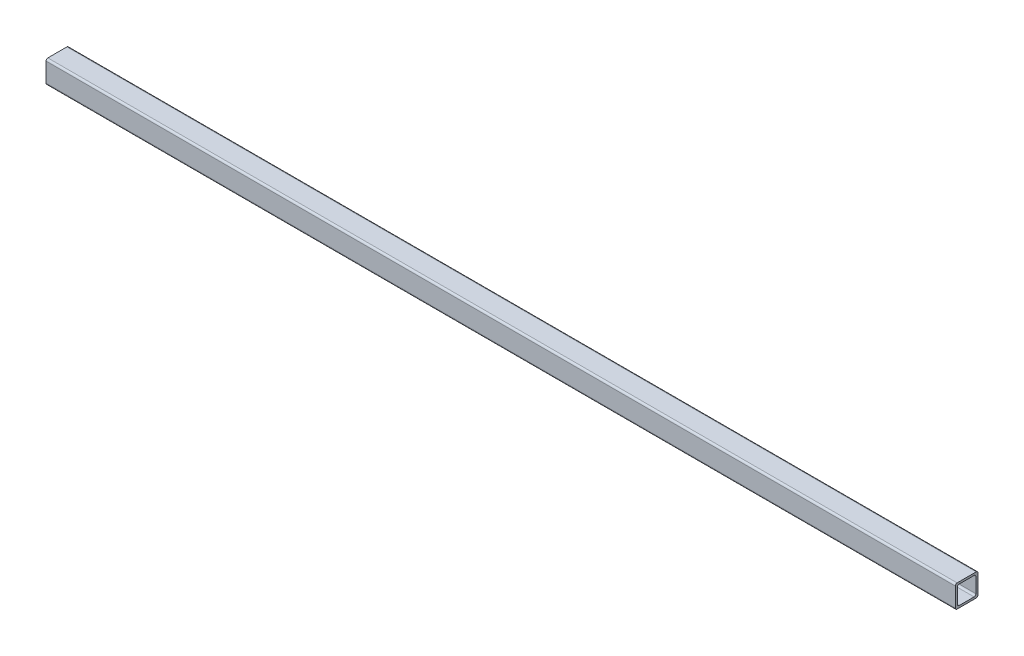
SolidWorks part; units mm, degrees
ref_plane "Front Plane" through (0, 0, 0) normal (0, 0, 1) x (1, 0, 0)
ref_plane "Top Plane" through (0, 0, 0) normal (0, 1, 0) x (1, 0, 0)
ref_plane "Right Plane" through (0, 0, 0) normal (1, 0, 0) x (0, 0, -1)
sketch "Sketch1" plane through (0, 0, 0) normal (1, 0, 0) x (0, 0, -1)
  line L1 (-12.5, 25) -> (12.5, 25)
  line L2 (-12.5, 25) -> (-12.5, 0)
  line L3 (-12.5, 0) -> (12.5, 0)
  line L4 (12.5, 25) -> (12.5, 0)
  dimension "D1" = 25
  dimension "D2" = 25
extrude "Boss-Extrude1" add sketch "Sketch1" along normal mid plane 1000
fillet "Fillet1" radius 2 4 edges at (0, 0, 12.5) (0, 0, -12.5) (0, 25, -12.5) (0, 25, 12.5)
sketch "Sketch2" plane through (500, 0, 0) normal (1, 0, 0) x (0, 0, -1)
  line L12 (-10.2, 22.7) -> (-10.2, 2.3)
  line L13 (-10.2, 2.3) -> (10.2, 2.3)
  line L14 (10.2, 2.3) -> (10.2, 22.7)
  line L15 (10.2, 22.7) -> (-10.2, 22.7)
extrude "Cut-Extrude1" cut sketch "Sketch2" against normal through all both and the other way through all
fillet "Fillet2" radius 2 4 edges at (0, 2.3, 10.2) (0, 22.7, 10.2) (0, 2.3, -10.2) (0, 22.7, -10.2)
